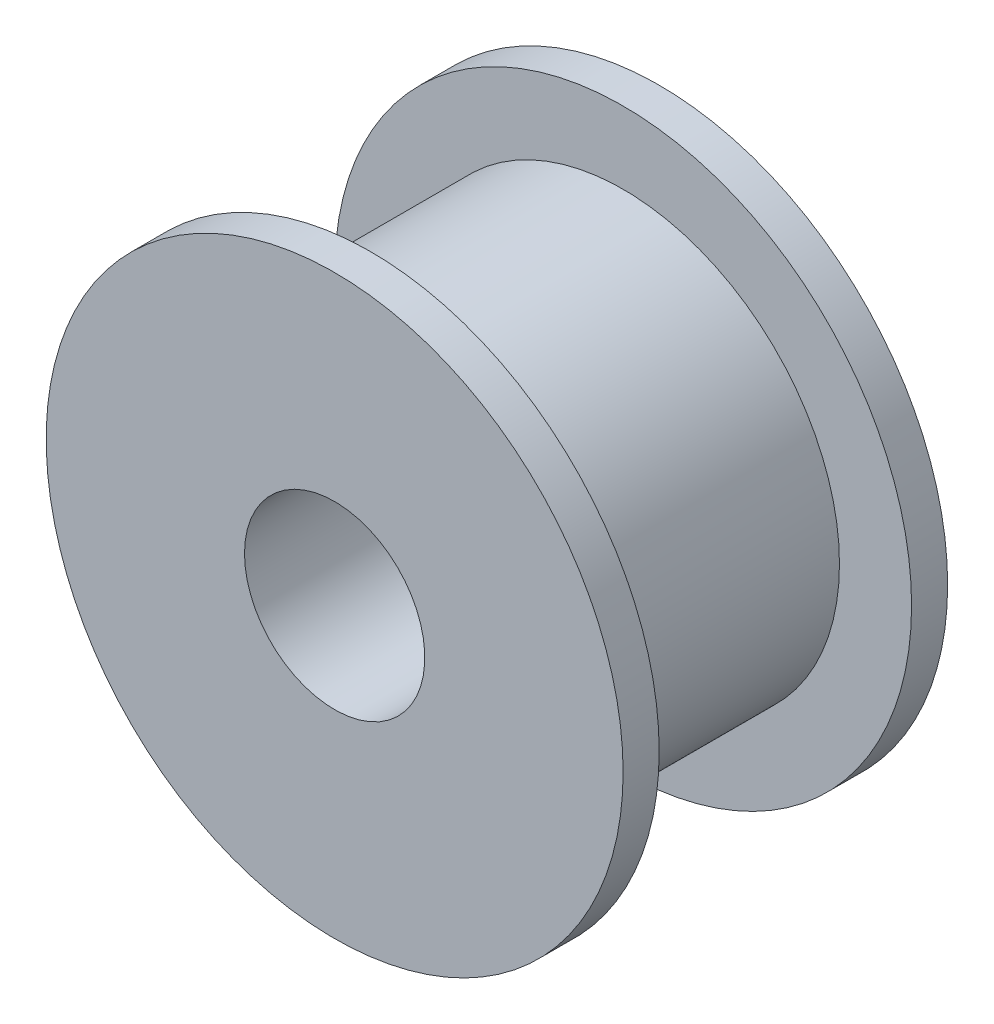
SolidWorks part; units mm, degrees
ref_plane "Front Plane" through (0, 0, 0) normal (0, 0, 1) x (1, 0, 0)
ref_plane "Top Plane" through (0, 0, 0) normal (0, 1, 0) x (1, 0, 0)
ref_plane "Right Plane" through (0, 0, 0) normal (1, 0, 0) x (0, 0, -1)
sketch "Sketch3" plane through (0, 0, 0) normal (0, 0, 1) x (1, 0, 0)
  circle A0 centre (0, 0) radius 8
  dimension "D1" = 16
extrude "Boss-Extrude1" add sketch "Sketch3" along normal mid plane 9
sketch "Sketch4" plane through (0, 0, -4.5) normal (0, 0, -1) x (-1, 0, 0)
  circle A0 centre (0, 0) radius 2.5
  dimension "D1" = 5
extrude "Cut-Extrude1" cut sketch "Sketch4" against normal through all
sketch "Sketch6" plane through (0, 0, 0) normal (0, 0, 1) x (1, 0, 0)
  circle A0 centre (0, 0) radius 8
  circle A1 centre (0, 0) radius 6
  dimension "D1" = 12
extrude "Cut-Extrude2" cut sketch "Sketch6" against normal mid plane 7
